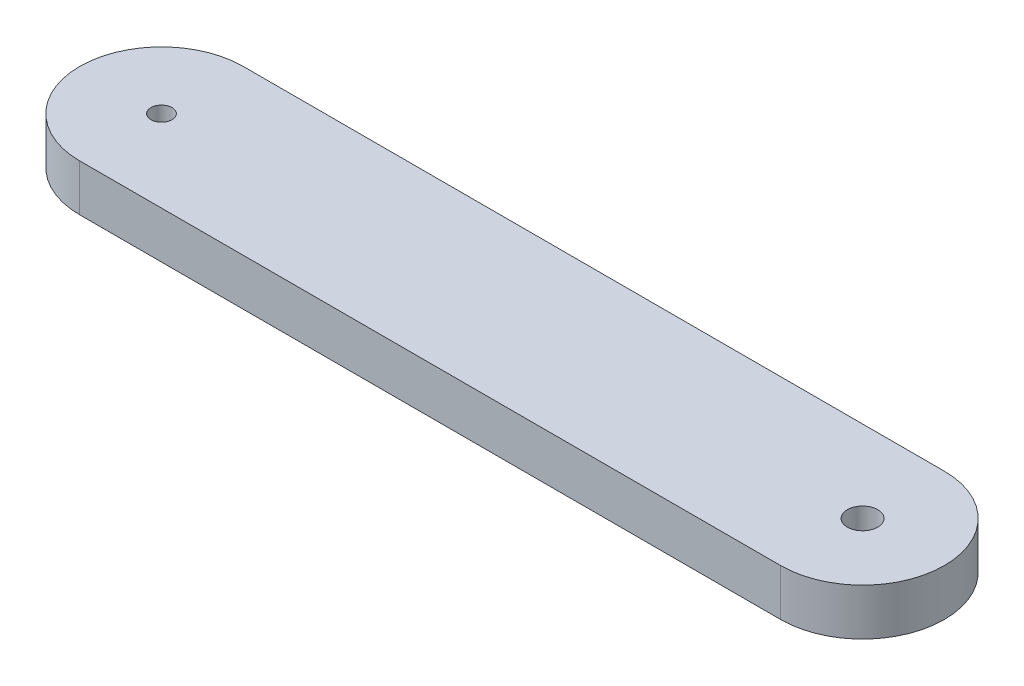
SolidWorks part; units mm, degrees
ref_plane "Front Plane" through (0, 0, 0) normal (0, 0, 1) x (1, 0, 0)
ref_plane "Top Plane" through (0, 0, 0) normal (0, 1, 0) x (1, 0, 0)
ref_plane "Right Plane" through (0, 0, 0) normal (1, 0, 0) x (0, 0, -1)
sketch "Sketch1" plane through (0, 0, 0) normal (0, 1, 0) x (1, 0, 0)
  line L0 (0, 0) -> (150, 0) construction
  line L1 (0, 17.5) -> (150, 17.5)
  line L2 (0, -17.5) -> (150, -17.5)
  arc A0 (0, 17.5) -> (0, -17.5) centre (0, 0) ccw
  arc A1 (150, -17.5) -> (150, 17.5) centre (150, 0) ccw
  circle A2 centre (0, 0) radius 2.25
  circle A3 centre (150, 0) radius 3.25
  point P3 (75, 0)
  dimension "D1" = 4.5
  dimension "D2" = 6.5
  dimension "D3" = 35
  dimension "D4" = 150
extrude "Boss-Extrude1" add sketch "Sketch1" along normal blind 10
